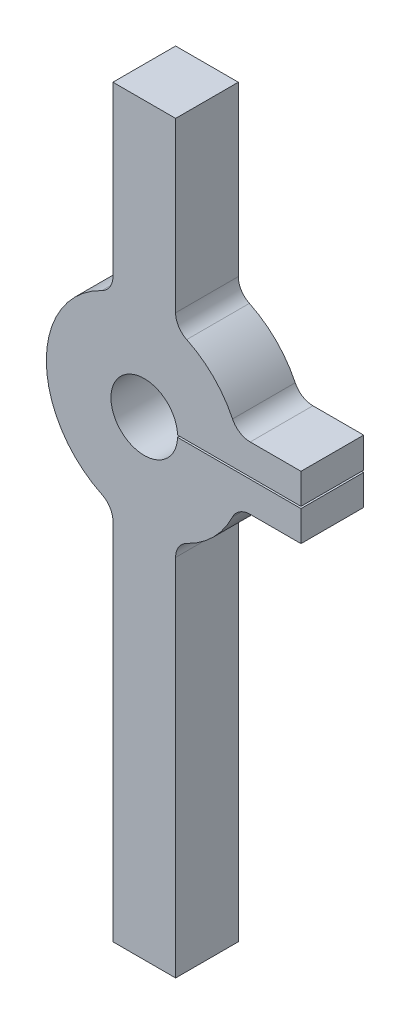
SolidWorks part; units mm, degrees
ref_plane "Front Plane" through (0, 0, 0) normal (0, 0, 1) x (1, 0, 0)
ref_plane "Top Plane" through (0, 0, 0) normal (0, 1, 0) x (1, 0, 0)
ref_plane "Right Plane" through (0, 0, 0) normal (1, 0, 0) x (0, 0, -1)
sketch "Sketch1" plane through (0, 0, 0) normal (0, 0, 1) x (1, 0, 0)
  circle A0 centre (0, 0) radius 8.5
  circle A1 centre (0, 0) radius 25
  dimension "D1" = 17
  dimension "D2" = 50
extrude "Boss-Extrude1" add sketch "Sketch1" along normal mid plane 16
sketch "Sketch2" plane through (0, 0, 0) normal (0, 0, 1) x (1, 0, 0)
  line L0 (0, 0) -> (0, 40.1669) construction
  line L1 (-8, 70) -> (8, 70)
  line L2 (8, 70) -> (8, 23.6854)
  line L3 (8, 23.6854) -> (-8, 23.6854)
  line L4 (-8, 70) -> (-8, 23.6854)
  circle A0 centre (0, 0) radius 25 construction
  point P10 (0, 23.6854)
  point P11 (0, 70)
  dimension "D1" = 16
  dimension "D2" = 70
extrude "Boss-Extrude2" add sketch "Sketch2" along normal mid plane 16
sketch "Sketch3" plane through (0, 0, 0) normal (0, 0, 1) x (1, 0, 0)
  line L0 (0, 0) -> (0, -28.6568) construction
  line L1 (-8, -120) -> (8, -120)
  line L2 (8, -120) -> (8, -23.6854)
  line L3 (8, -23.6854) -> (-8, -23.6854)
  line L4 (-8, -120) -> (-8, -23.6854)
  arc A0 (-8, 23.6854) -> (8, 23.6854) centre (0, 0) ccw construction
  point P11 (0, -23.6854)
  point P12 (0, -120)
  dimension "D1" = 16
  dimension "D2" = 120
extrude "Boss-Extrude3" add sketch "Sketch3" along normal mid plane 16
sketch "Sketch4" plane through (0, 0, 0) normal (0, 0, 1) x (1, 0, 0)
  line L0 (0, 0) -> (85.7397, 0) construction
  line L1 (40, -8) -> (40, 8)
  line L2 (40, 8) -> (23.6854, 8)
  line L3 (23.6854, 8) -> (23.6854, -8)
  line L4 (40, -8) -> (23.6854, -8)
  circle A0 centre (0, 0) radius 25 construction
  point P11 (40, 0)
  point P12 (23.6854, 0)
  dimension "D1" = 16
  dimension "D2" = 40
extrude "Boss-Extrude4" add sketch "Sketch4" along normal mid plane 16
sketch "Sketch5" plane through (0, 0, 0) normal (0, 0, 1) x (1, 0, 0)
  line L0 (0, 0) -> (67.4641, 0) construction
  line L1 (2, -0.25) -> (2, 0.25)
  line L2 (2, 0.25) -> (50, 0.25)
  line L3 (50, 0.25) -> (50, -0.25)
  line L4 (2, -0.25) -> (50, -0.25)
  point P8 (50, 0)
  point P9 (2, 0)
  dimension "D1" = 0.5
  dimension "D2" = 50
  dimension "D3" = 2
extrude "Cut-Extrude1" cut sketch "Sketch5" against normal through all both and the other way through all
fillet "Fillet1" radius 5 6 edges at (-8, -23.6854, 0) (-8, 23.6854, 0) (8, -23.6854, 0) (23.6854, 8, 0) (8, 23.6854, 0) (23.6854, -8, 0)
sketch "Sketch7" plane through (0, 0, 0) normal (1, 0, 0) x (0, 0, -1)
  line L0 (0, 0) -> (12.2593, 0) construction
  line L1 (5, 8.5) -> (5, 14)
  line L2 (8, 8.5) -> (-8, 8.5) construction
  line L3 (5, 14) -> (8, 14)
  line L4 (8, 10.8333) -> (8, 22.5308) construction
  line L5 (8, 14) -> (8, 8.5)
  line L6 (8, 8) -> (8, 10.8333) construction
  line L7 (8, 8.5) -> (5, 8.5)
  dimension "D1" = 3
  dimension "D2" = 14
revolve "Cut-Revolve1" cut sketch "Sketch7" angle 360 about L0
